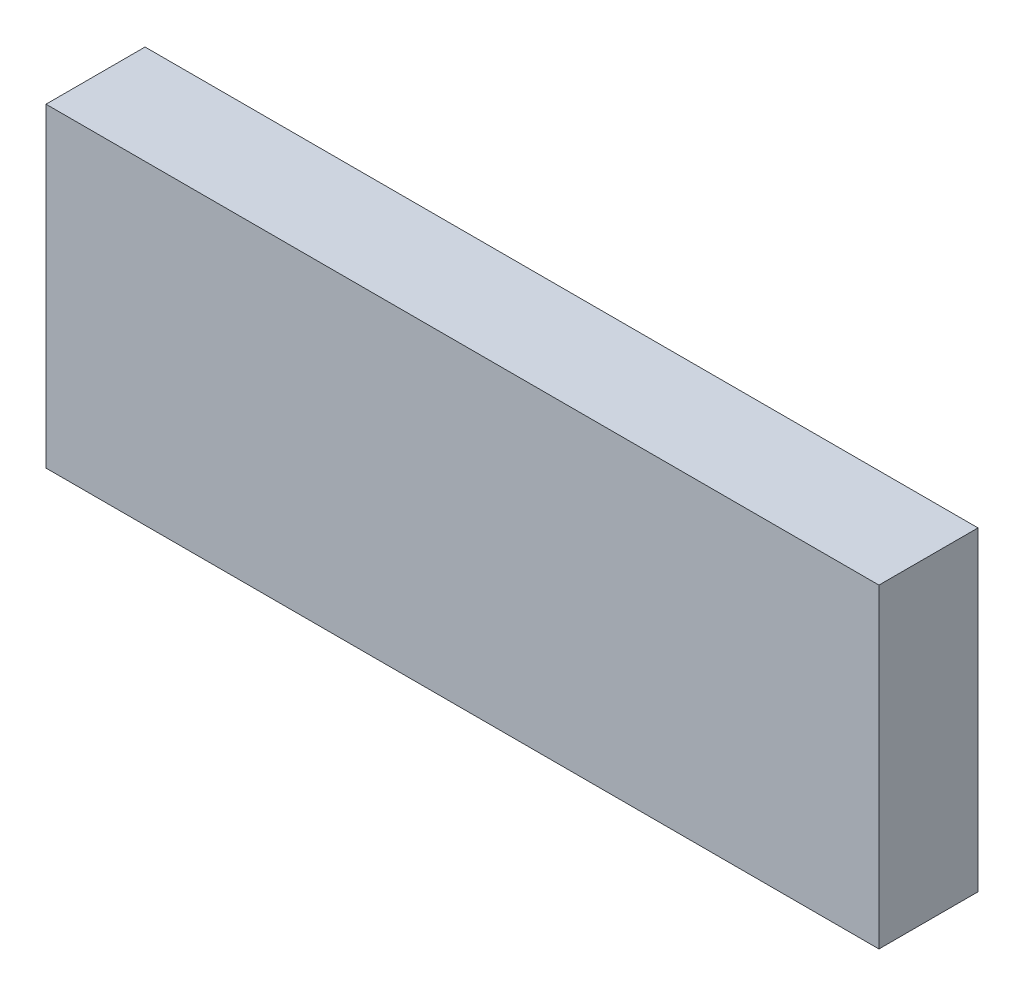
SolidWorks part; units mm, degrees
ref_plane "Plan de face" through (0, 0, 0) normal (0, 0, 1) x (1, 0, 0)
ref_plane "Plan de dessus" through (0, 0, 0) normal (0, 1, 0) x (1, 0, 0)
ref_plane "Plan de droite" through (0, 0, 0) normal (1, 0, 0) x (0, 0, -1)
sketch "Esquisse1" plane through (0, 0, 0) normal (0, 1, 0) x (1, 0, 0)
  line L1 (-92.5, -11) -> (92.5, -11)
  line L2 (-92.5, -11) -> (-92.5, 11)
  line L3 (-92.5, 11) -> (92.5, 11)
  line L4 (92.5, -11) -> (92.5, 11)
  line L5 (-92.5, -11) -> (92.5, 11) construction
  line L6 (-92.5, 11) -> (92.5, -11) construction
  point P0 (0, 0)
  dimension "D1" = 22
  dimension "D2" = 185
extrude "Boss.-Extru.1" add sketch "Esquisse1" along normal blind 70
